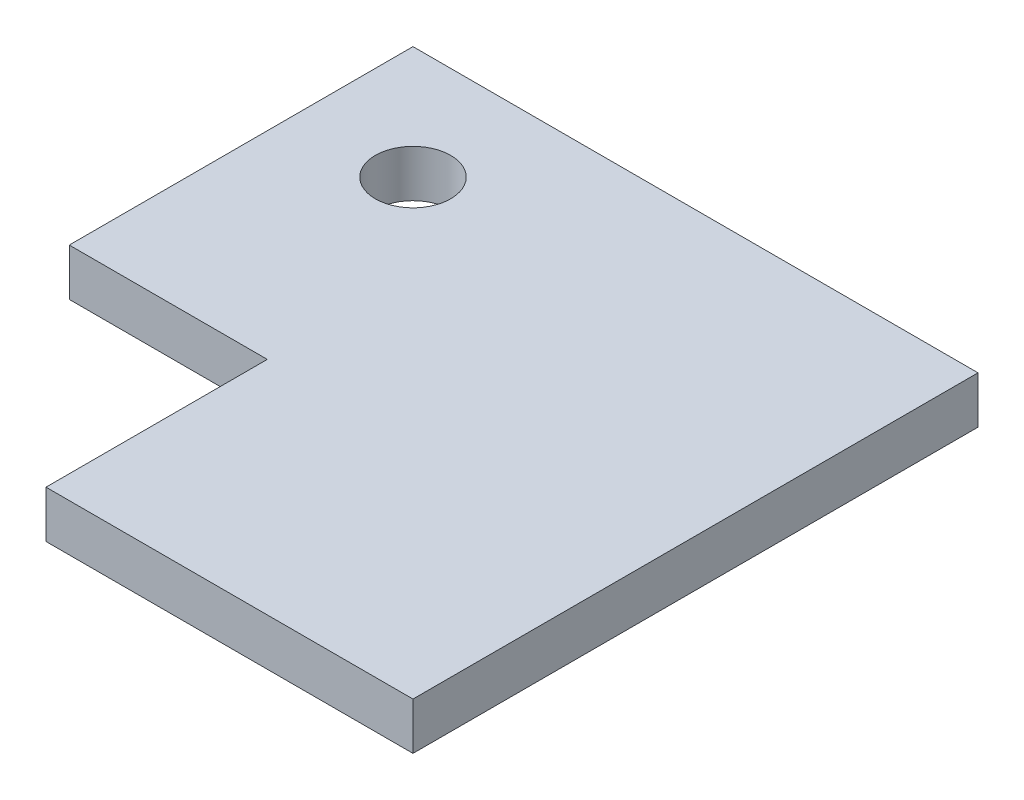
SolidWorks part; units mm, degrees
ref_plane "前视基准面" through (0, 0, 0) normal (0, 0, 1) x (1, 0, 0)
ref_plane "上视基准面" through (0, 0, 0) normal (0, 1, 0) x (1, 0, 0)
ref_plane "右视基准面" through (0, 0, 0) normal (1, 0, 0) x (0, 0, -1)
sketch "草图1" plane through (0, 0, 0) normal (0, 1, 0) x (1, 0, 0)
  line L1 (0, 0) -> (60, 0)
  line L2 (0, 0) -> (0, -60)
  line L3 (0, -60) -> (60, -60)
  line L4 (60, 0) -> (60, -60)
  circle A0 centre (12, -12) radius 4
  dimension "D1" = 8
  dimension "D2" = 12
  dimension "D3" = 12
  dimension "D4" = 60
  dimension "D5" = 60
extrude "凸台-拉伸1" add sketch "草图1" along normal blind 5
sketch "草图2" plane through (0, 0, 0) normal (0, 1, 0) x (1, 0, 0)
  line L1 (0, -60) -> (21.03, -60)
  line L2 (0, -60) -> (0, -36.5)
  line L3 (0, -36.5) -> (21.03, -36.5)
  line L4 (21.03, -60) -> (21.03, -36.5)
  dimension "D1" = 23.5
  dimension "D2" = 21.03
extrude "切除-拉伸1" cut sketch "草图2" along normal through all
